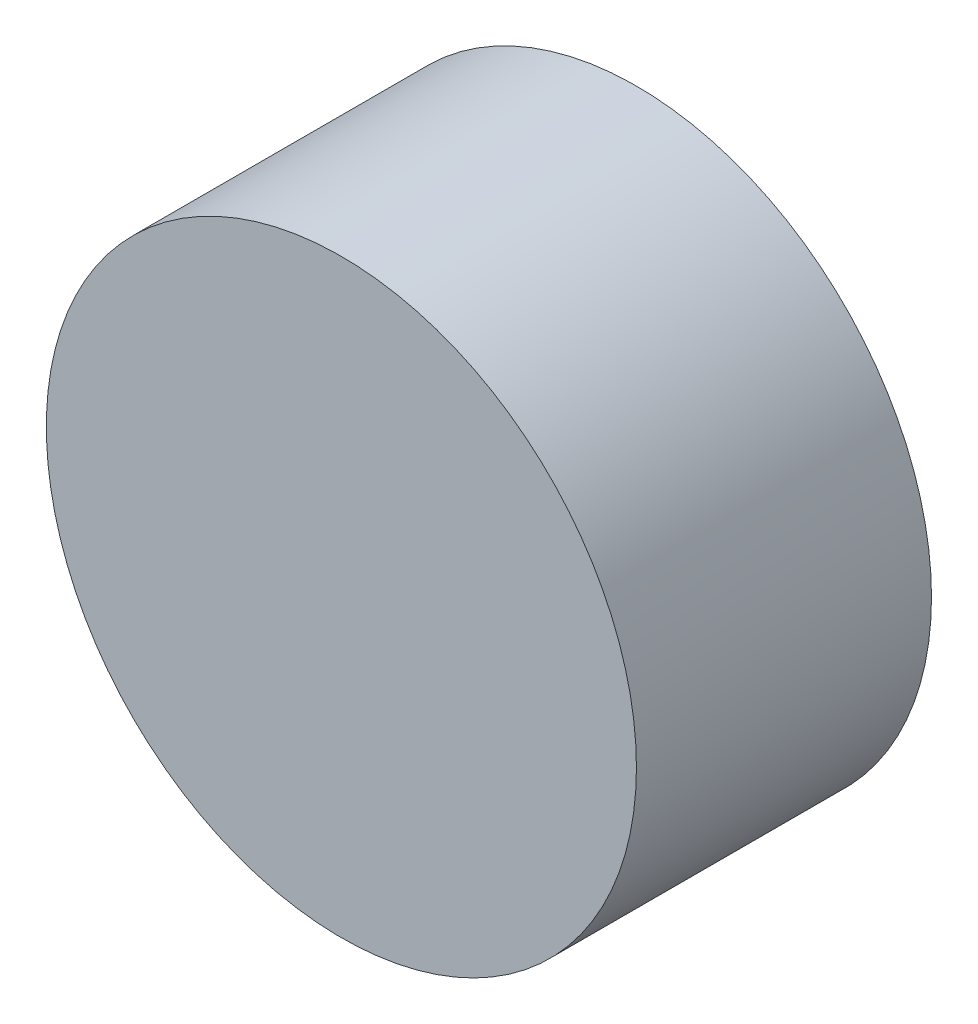
SolidWorks part; units mm, degrees
ref_plane "前视基准面" through (0, 0, 0) normal (0, 0, 1) x (1, 0, 0)
ref_plane "上视基准面" through (0, 0, 0) normal (0, 1, 0) x (1, 0, 0)
ref_plane "右视基准面" through (0, 0, 0) normal (1, 0, 0) x (0, 0, -1)
other "Configuration Table"
sketch "草图1" plane through (0, 0, 0) normal (0, 0, 1) x (1, 0, 0)
  circle A0 centre (0, 0) radius 10
extrude "凸台-拉伸1" add sketch "草图1" along normal blind 10
